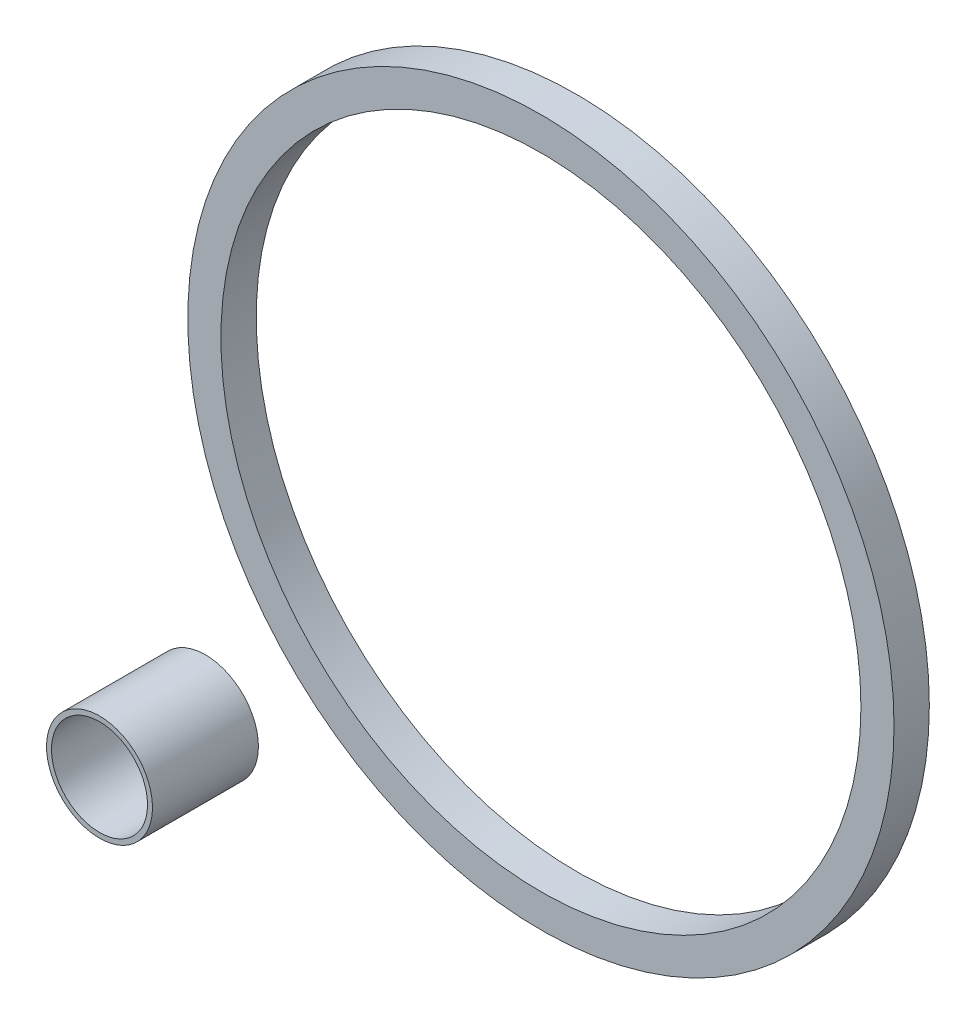
SolidWorks part; units mm, degrees
material "Copper"
ref_plane "Front Plane" through (0, 0, 0) normal (0, 0, 1) x (1, 0, 0)
ref_plane "Top Plane" through (0, 0, 0) normal (0, 1, 0) x (1, 0, 0)
ref_plane "Right Plane" through (0, 0, 0) normal (1, 0, 0) x (0, 0, -1)
sketch3d "3DSketch1" plane through (0, 0, 0) normal (0, 0, 1) x (1, 0, 0)
  dimension "D1" = 200
  dimension "D2" = 400
  dimension "D3" = 600
  dimension "D4" = 800
  dimension "D5" = 1000
sketch "Sketch3" plane through (0, 0, 200) normal (0, 0, 1) x (1, 0, 0)
  circle A0 centre (0, 0) radius 1000
extrude "Boss-Extrude2" add sketch "Sketch3" along normal blind 2000
sketch "Sketch8" plane through (0, 0, 0) normal (0, 0, 1) x (1, 0, 0)
  circle A0 centre (0, 0) radius 1000
extrude "Boss-Extrude7" add sketch "Sketch8" along normal blind 100 separate body
sketch "Sketch9" plane through (0, 0, 0) normal (0, 0, 1) x (1, 0, 0)
  circle A0 centre (0, 0) radius 906.211
extrude "Cut-Extrude3" cut sketch "Sketch9" along normal blind 6000
scale "Scale5" bodies to scale 113 scale about centroid uniform scaling yes scale factor 0.15
